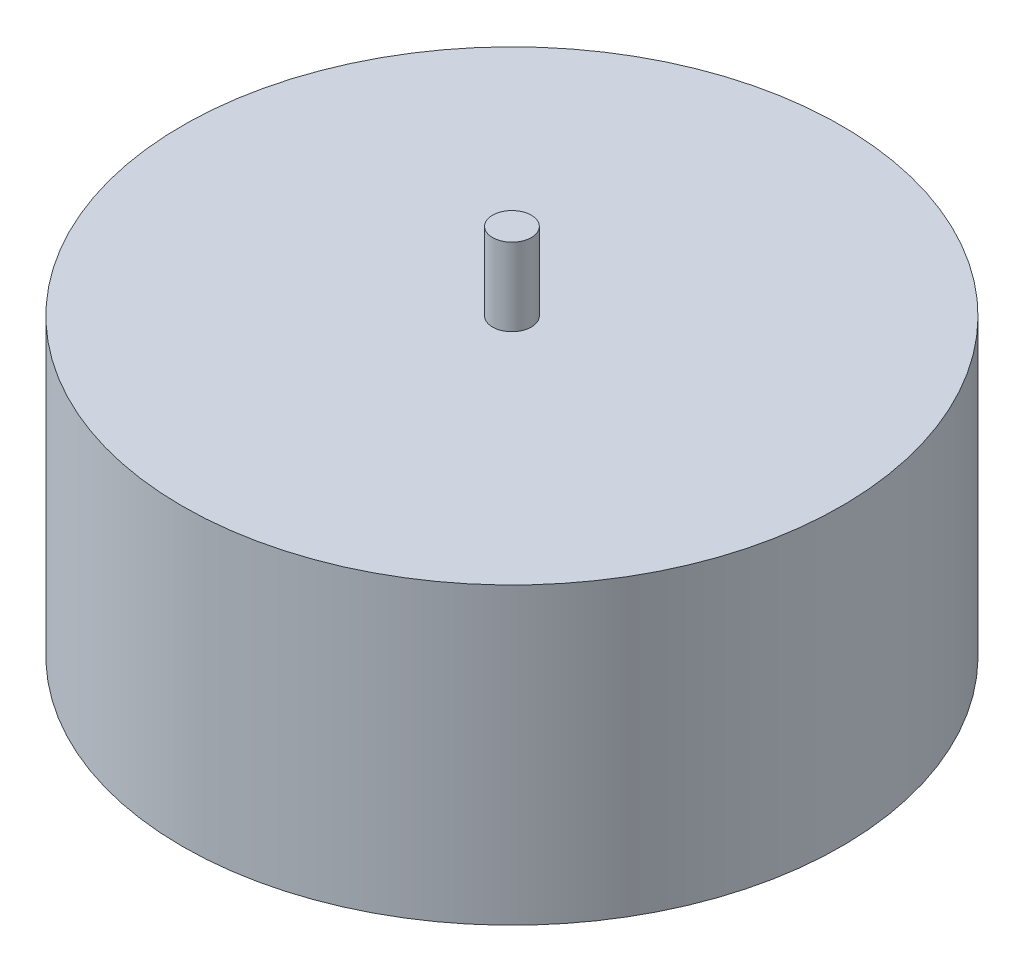
SolidWorks part; units mm, degrees
ref_plane "Front Plane" through (0, 0, 0) normal (0, 0, 1) x (1, 0, 0)
ref_plane "Top Plane" through (0, 0, 0) normal (0, 1, 0) x (1, 0, 0)
ref_plane "Right Plane" through (0, 0, 0) normal (1, 0, 0) x (0, 0, -1)
sketch "Sketch1" plane through (0, 0, 0) normal (0, 1, 0) x (1, 0, 0)
  circle A0 centre (0, 0) radius 42.5
  dimension "D1" = 85
extrude "Boss-Extrude1" add sketch "Sketch1" along normal blind 38
sketch "Sketch2" plane through (0, 38, 0) normal (0, 1, 0) x (1, 0, 0)
  circle A0 centre (0, 0) radius 2.5
  dimension "D1" = 5
extrude "Boss-Extrude2" add sketch "Sketch2" along normal blind 10
